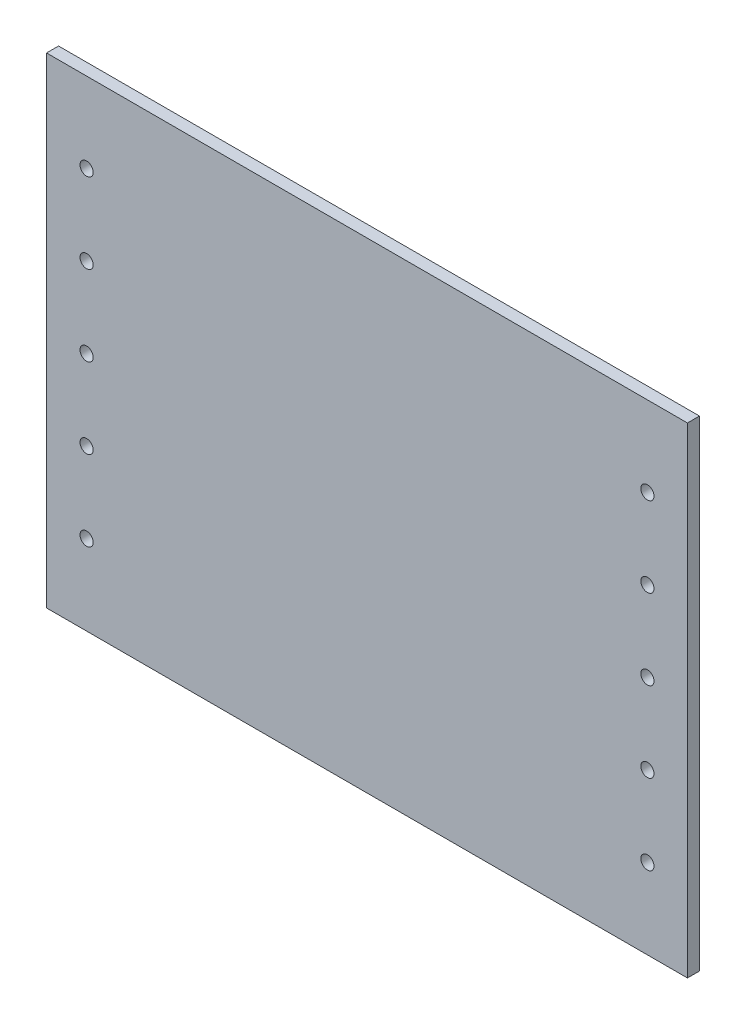
SolidWorks part; units mm, degrees
ref_plane "前视基准面" through (0, 0, 0) normal (0, 0, 1) x (1, 0, 0)
ref_plane "上视基准面" through (0, 0, 0) normal (0, 1, 0) x (1, 0, 0)
ref_plane "右视基准面" through (0, 0, 0) normal (1, 0, 0) x (0, 0, -1)
other "Configuration Table"
sketch "草图1" plane through (0, 0, 0) normal (0, 0, 1) x (1, 0, 0)
  line L0 (0, -55) -> (0, 55) construction
  line L1 (-80, 60) -> (80, 60)
  line L2 (-80, 60) -> (-80, -60)
  line L3 (-80, -60) -> (80, -60)
  line L4 (80, 60) -> (80, -60)
  line L5 (-80, 60) -> (80, -60) construction
  line L6 (-80, -60) -> (80, 60) construction
  circle A2 centre (-70, 40) radius 1.65
  circle A3 centre (-70, 20) radius 1.65
  circle A4 centre (-70, 0) radius 1.65
  circle A5 centre (-70, -20) radius 1.65
  circle A6 centre (-70, -40) radius 1.65
  circle A7 centre (70, -40) radius 1.65
  circle A8 centre (70, -20) radius 1.65
  circle A9 centre (70, 0) radius 1.65
  circle A10 centre (70, 20) radius 1.65
  circle A11 centre (70, 40) radius 1.65
  point P0 (0, 0)
  dimension "D3" = 3.3
  dimension "D5" = 10
  dimension "D1" = 160
  dimension "D2" = 120
  dimension "D4" = 20
  dimension "D6" = 5
extrude "凸台-拉伸1" add sketch "草图1" along normal blind 3
